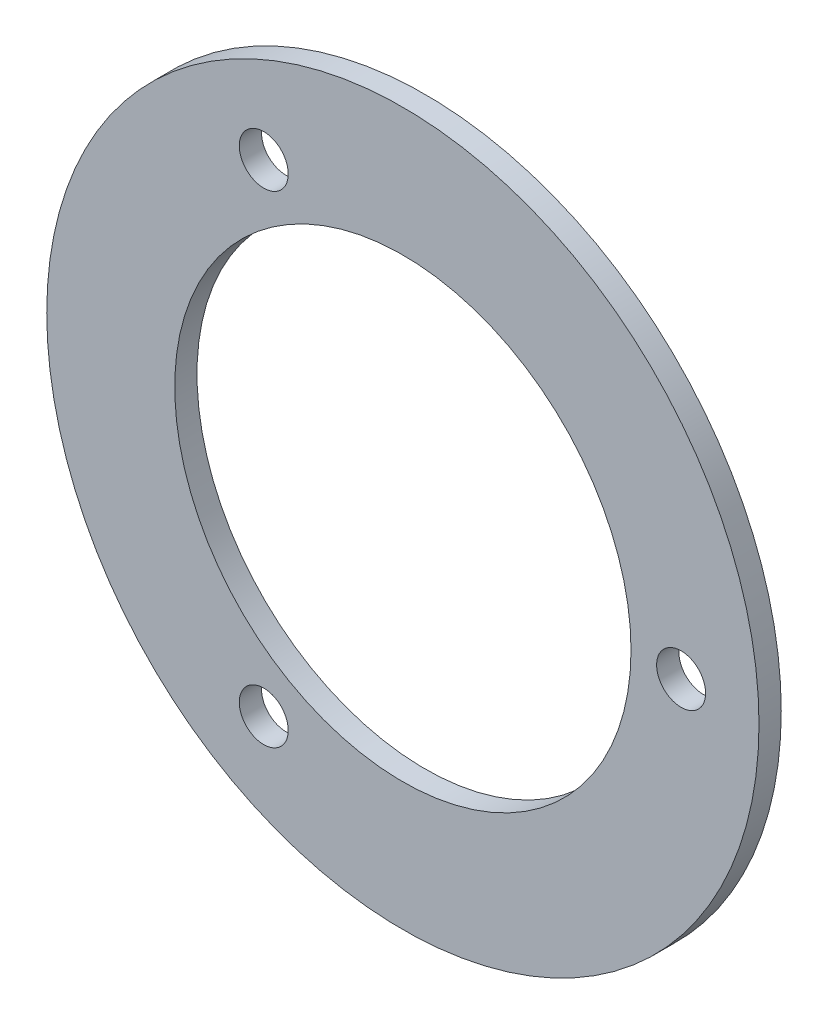
SolidWorks part; units mm, degrees
ref_plane "Front Plane" through (0, 0, 0) normal (0, 0, 1) x (1, 0, 0)
ref_plane "Top Plane" through (0, 0, 0) normal (0, 1, 0) x (1, 0, 0)
ref_plane "Right Plane" through (0, 0, 0) normal (1, 0, 0) x (0, 0, -1)
sketch "Sketch1" plane through (0, 0, 0) normal (0, 0, 1) x (1, 0, 0)
  circle A0 centre (0, 0) radius 10.25
  circle A1 centre (0, 0) radius 16
extrude "Boss-Extrude1" add sketch "Sketch1" along normal blind 1
sketch "Sketch2" plane through (0, 0, 0) normal (0, 0, -1) x (-1, 0, 0)
  circle A0 centre (-12.5, 0) radius 1.1
  circle A1 centre (6.25, 10.8253) radius 1.1
  circle A2 centre (6.25, -10.8253) radius 1.1
extrude "Retainer_Three_D2p2" cut sketch "Sketch2" against normal blind 1.01
